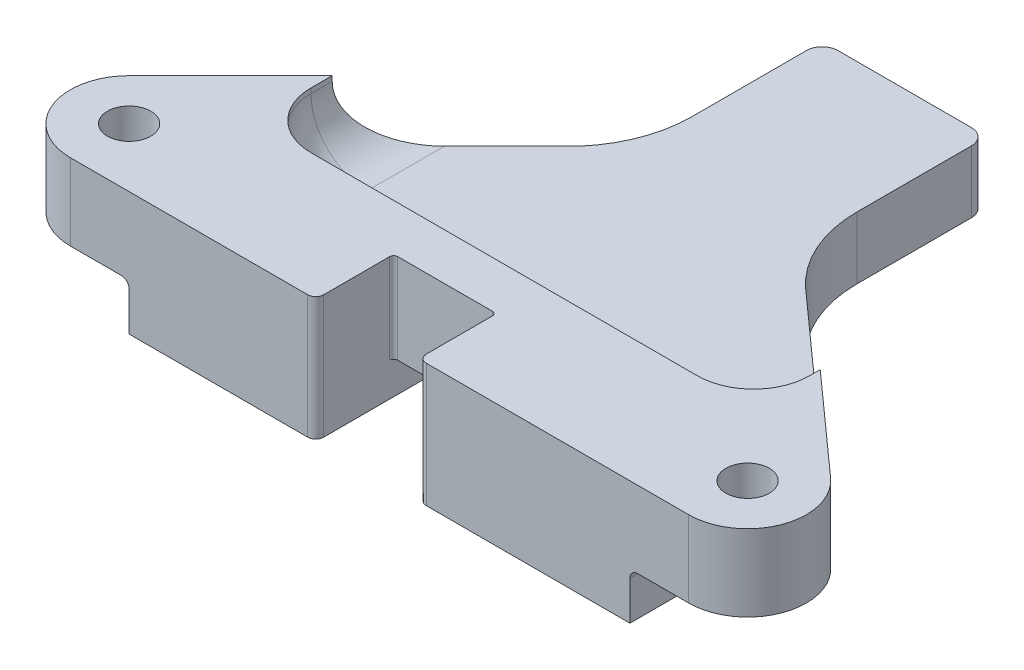
SolidWorks part; units mm, degrees
material "Nylon 6/10"
ref_plane "Front Plane" through (0, 0, 0) normal (0, 0, 1) x (1, 0, 0)
ref_plane "Top Plane" through (0, 0, 0) normal (0, 1, 0) x (1, 0, 0)
ref_plane "Right Plane" through (0, 0, 0) normal (1, 0, 0) x (0, 0, -1)
sketch "Sketch1" plane through (0, 0, 0) normal (0, 1, 0) x (1, 0, 0)
  line L1 (-31.5087, -42.4942) -> (31.5087, -42.4942)
  line L2 (-37.5031, -36.4998) -> (-37.5031, 36.4998)
  line L3 (-31.5087, 42.4942) -> (31.5087, 42.4942)
  line L4 (37.5031, -36.4998) -> (37.5031, 36.4998)
  line L6 (-37.5031, 42.4942) -> (37.5031, -42.4942) construction
  line L7 (-31.5087, -36.4998) -> (31.5087, -36.4998) construction
  line L8 (-31.5087, -36.4998) -> (-31.5087, 36.4998) construction
  line L9 (-31.5087, 36.4998) -> (31.5087, 36.4998) construction
  line L10 (31.5087, -36.4998) -> (31.5087, 36.4998) construction
  line L11 (-31.5087, -36.4998) -> (31.5087, 36.4998) construction
  line L12 (-31.5087, 36.4998) -> (31.5087, -36.4998) construction
  arc A0 (-31.5087, 42.4942) -> (-37.5031, 36.4998) centre (-31.5087, 36.4998) ccw
  arc A1 (-37.5031, -36.4998) -> (-31.5087, -42.4942) centre (-31.5087, -36.4998) ccw
  arc A2 (37.5031, -36.4998) -> (31.5087, -42.4942) centre (31.5087, -36.4998) cw
  circle A3 centre (-31.5087, 36.4998) radius 2.2098
  circle A4 centre (31.5087, 36.4998) radius 2.2098
  circle A5 centre (31.5087, -36.4998) radius 2.2098
  circle A6 centre (-31.5087, -36.4998) radius 2.2098
  arc A7 (37.5031, 36.4998) -> (31.5087, 42.4942) centre (31.5087, 36.4998) ccw
  point P0 (0, 0)
  point P1 (0, 0)
  point P15 (0, 0)
  point P27 (0, 0)
  point P28 (0, 0)
  point P29 (0, 0)
  point P30 (0, 0)
  point P31 (0, 0)
  point P32 (0, 0)
  point P33 (0, 0)
  point P34 (-28.7739, -33.5876)
  dimension "D3" = 5.9944
  dimension "D4" = 4.4196
  dimension "D1" = 75.0062
  dimension "D2" = 84.9884
extrude "Boss-Extrude1" add sketch "Sketch1" along normal blind 12.573
sketch "Sketch2" plane through (0, 0, 0) normal (0, 1, 0) x (1, 0, 0)
  line L0 (-31.5087, -42.4942) -> (31.5087, -42.4942) construction
  line L1 (-6.5024, -42.4942) -> (3.9624, -42.4942)
  line L2 (-6.5024, -42.4942) -> (-6.5024, 8.7122)
  line L3 (-6.096, 9.1186) -> (3.556, 9.1186)
  line L4 (3.9624, -42.4942) -> (3.9624, 8.7122)
  line L5 (-6.5024, -42.4942) -> (3.9624, 9.1186) construction
  line L6 (-6.5024, 9.1186) -> (3.9624, -42.4942) construction
  arc A0 (3.9624, 8.7122) -> (3.556, 9.1186) centre (3.556, 8.7122) ccw
  arc A1 (-6.5024, 8.7122) -> (-6.096, 9.1186) centre (-6.096, 8.7122) cw
  point P0 (-1.27, -16.6878)
  point P15 (-1.27, 9.1186)
  dimension "D4" = 0.4064
  dimension "D1" = 51.6128
  dimension "D2" = 10.4648
  dimension "D3" = 1.27
extrude "Cut-Extrude1" cut sketch "Sketch2" along normal blind 3.429 and the other way through all
sketch "Sketch8" plane through (0, 0, 0) normal (0, -1, 0) x (1, 0, 0)
  line L0 (3.9624, 42.4942) -> (3.9624, -8.7122) construction
  line L1 (-6.5024, 42.4942) -> (3.9624, 42.4942)
  line L2 (-6.5024, 42.4942) -> (-6.5024, 34.9504)
  line L3 (-6.096, 34.544) -> (3.556, 34.544)
  line L4 (3.9624, 42.4942) -> (3.9624, 34.9504)
  arc A0 (3.9624, 34.9504) -> (3.556, 34.544) centre (3.556, 34.9504) cw
  arc A1 (-6.5024, 34.9504) -> (-6.096, 34.544) centre (-6.096, 34.9504) ccw
  point P9 (3.9624, 34.544)
  dimension "D1" = 0.4064
  dimension "D2" = 7.9502
extrude "Cut-Extrude5" cut sketch "Sketch8" against normal through all both and the other way through all
sketch "Sketch9" plane through (0, 0, 0) normal (0, -1, 0) x (1, 0, 0)
  line L0 (-8.0772, -12.2936) -> (5.5372, -12.2936)
  line L1 (7.1374, -10.6934) -> (7.1374, 0.9673)
  line L2 (11.3681, 10.4309) -> (35.5062, 32.033)
  line L5 (37.5031, 36.4998) -> (37.5031, -42.4942)
  line L6 (37.5031, -42.4942) -> (-37.5031, -42.4942)
  line L7 (-9.6774, -10.6934) -> (-9.6774, 0.9673)
  line L11 (-37.5031, 36.4998) -> (-37.5031, -42.4942)
  line L12 (-9.6774, -4.8631) -> (-6.5024, -4.8631) construction
  line L13 (-6.5024, -8.7122) -> (-6.5024, 42.4942) construction
  line L14 (7.1374, -4.8631) -> (3.9624, -4.8631) construction
  line L15 (3.9624, 34.9504) -> (3.9624, -8.7122) construction
  line L16 (31.5087, -42.4942) -> (-31.5087, -42.4942) construction
  line L17 (3.556, -9.1186) -> (-6.096, -9.1186) construction
  line L18 (-35.7474, 32.2611) -> (-12.8421, 9.3559)
  arc A0 (7.1374, 0.9673) -> (11.3681, 10.4309) centre (19.8374, 0.9673) cw
  arc A1 (-9.6774, 0.9673) -> (-12.8421, 9.3559) centre (-22.3774, 0.9673) ccw
  arc A2 (7.1374, -10.6934) -> (5.5372, -12.2936) centre (5.5372, -10.6934) cw
  arc A3 (-8.0772, -12.2936) -> (-9.6774, -10.6934) centre (-8.0772, -10.6934) cw
  circle A4 centre (31.5087, 36.4998) radius 5.9944 construction
  arc A5 (37.5031, 36.4998) -> (31.5087, 42.4942) centre (31.5087, 36.4998) ccw construction
  circle A6 centre (-31.5087, 36.4998) radius 5.9944 construction
  arc A7 (-37.5031, 36.4998) -> (-35.7474, 32.2611) centre (-31.5087, 36.4998) ccw
  arc A8 (37.5031, 36.4998) -> (35.5062, 32.033) centre (31.5087, 36.4998) cw
  point P4 (0, 0)
  point P5 (7.1374, -1.6094)
  dimension "D1" = 12.7
  dimension "D2" = 1.6002
  dimension "D3" = 135
  dimension "D4" = 3.175
  dimension "D5" = 3.175
extrude "Cut-Extrude6" cut sketch "Sketch9" against normal through all both and the other way through all
sketch "Sketch10" plane through (0, 0, -12.2936) normal (0, 0, -1) x (-1, 0, 0)
  line L0 (-35.5062, 12.573) -> (-11.3681, 12.573) construction
  line L1 (-25.4, 12.573) -> (25.4, 12.573)
  line L2 (-25.4, 12.573) -> (-25.4, 12.065)
  line L3 (-19.685, 6.35) -> (19.685, 6.35)
  line L4 (25.4, 12.573) -> (25.4, 12.065)
  line L5 (-11.3681, 0) -> (-35.5062, 0) construction
  line L6 (0, 6.9427) -> (0, -6.9427) construction
  arc A0 (25.4, 12.065) -> (19.685, 6.35) centre (19.685, 12.065) cw
  arc A1 (-25.4, 12.065) -> (-19.685, 6.35) centre (-19.685, 12.065) ccw
  point P12 (0, 6.35)
  point P13 (0, 0)
  dimension "D1" = 5.715
  dimension "D2" = 6.35
  dimension "D3" = 50.8
extrude "Cut-Extrude7" cut sketch "Sketch10" against normal offset from surface 12.7 and the other way through all contours L3 A0 L4 L1 L2 A1 up to face at (-19.0055, 6.2865, 42.4942)
fillet "Fillet4" radius 5.715 5 edges at (-25.4, 12.319, 29.7942) (-23.7261, 8.0239, 29.7942) (25.4, 12.319, 29.7942) (23.7261, 8.0239, 29.7942) (0, 6.35, 29.7942)
sketch "Sketch11" plane through (0, 0, 0) normal (0, -1, 0) x (1, 0, 0)
  line L0 (-25.5143, 36.4998) -> (-25.5143, 42.4942)
  line L1 (-31.5087, 42.4942) -> (-6.5024, 42.4942) construction
  line L2 (-25.5143, 42.4942) -> (-37.5031, 42.4942)
  line L3 (-37.5031, 42.4942) -> (-37.5031, 22.028)
  line L4 (-37.5031, 22.028) -> (-27.27, 32.2611)
  line L5 (-35.7474, 32.2611) -> (-12.8421, 9.3559) construction
  circle A0 centre (-31.5087, 36.4998) radius 5.9944 construction
  arc A1 (-31.5087, 42.4942) -> (-35.7474, 32.2611) centre (-31.5087, 36.4998) ccw construction
  arc A2 (-27.27, 32.2611) -> (-25.5143, 36.4998) centre (-31.5087, 36.4998) ccw
  line M11 (-6.5024, 42.4942) -> (-31.5087, 42.4942)
  arc M12 (-31.5087, 42.4942) -> (-35.7474, 32.2611) centre (-31.5087, 36.4998) ccw
  line M13 (-35.7474, 32.2611) -> (-12.8421, 9.3559)
  circle M22 centre (-31.5087, 36.4998) radius 2.2098
extrude "Cut-Extrude8" cut sketch "Sketch11" against normal blind 4.7752 and the other way through all contours L3 L4 M13 M12 | L4 A2 L0 M11 M12 M13 M22 | L2 L3 M12
mirror "Mirror1" about plane through (0, 0, 0) normal (1, 0, 0) of "Cut-Extrude8"
fillet "Fillet5" radius 0.8128 6 edges at (-25.5143, 4.7752, 39.497) (-25.9706, 4.7752, 34.2058) (29.2751, 4.7752, 30.256) (25.5143, 4.7752, 39.497) (-29.3894, 4.7752, 30.1418) (25.9706, 4.7752, 34.2058)
fillet "Fillet6" radius 0.8128 2 edges at (-6.5024, 6.2865, 42.4942) (3.9624, 6.2865, 42.4942)
